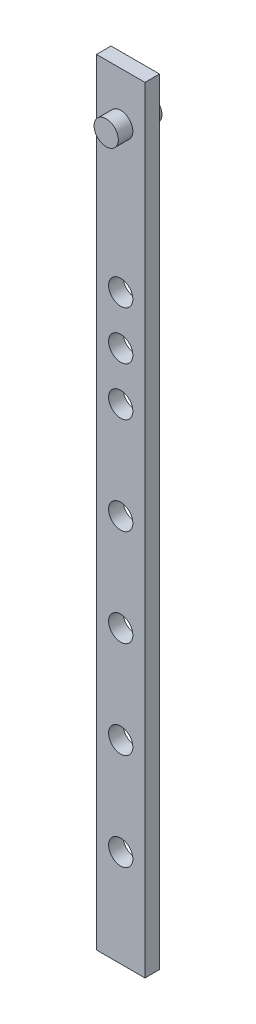
SolidWorks part; units mm, degrees
ref_plane "前基準面" through (0, 0, 0) normal (0, 0, 1) x (1, 0, 0)
ref_plane "上基準面" through (0, 0, 0) normal (0, 1, 0) x (1, 0, 0)
ref_plane "右基準面" through (0, 0, 0) normal (1, 0, 0) x (0, 0, -1)
sketch "草圖1" plane through (0, 0, 0) normal (0, 0, 1) x (1, 0, 0)
  line L0 (0, -80) -> (0, 80) construction
  line L1 (-5, -80) -> (5, -80)
  line L2 (-5, -80) -> (-5, 80)
  line L3 (-5, 80) -> (5, 80)
  line L4 (5, -80) -> (5, 80)
  line L5 (-5, -80) -> (5, 80) construction
  line L6 (-5, 80) -> (5, -80) construction
  circle A0 centre (0, -60) radius 2.5
  circle A1 centre (0, -40) radius 2.5
  circle A2 centre (0, -20) radius 2.5
  circle A3 centre (0, 0) radius 2.5
  circle A4 centre (0, 20) radius 2.5
  circle A5 centre (0, 40) radius 2.5
  circle A6 centre (0, 30) radius 2.5
  point P0 (0, 0)
  dimension "D3" = 20
  dimension "D9" = 5
  dimension "D11" = 10
  dimension "D10" = 5
  dimension "D1" = 160
  dimension "D2" = 10
  dimension "D4" = 20
  dimension "D5" = 20
  dimension "D6" = 20
  dimension "D7" = 20
  dimension "D8" = 20
extrude "填料-伸長1" add sketch "草圖1" along normal blind 3
sketch "草圖2" plane through (0, 0, 3) normal (0, 0, 1) x (1, 0, 0)
  line L1 (5, 80) -> (-5, 80) construction
  circle A0 centre (0, 70) radius 2.5
  dimension "D1" = 5
  dimension "D2" = 10
extrude "填料-伸長2" add sketch "草圖2" against normal blind 6 and the other way blind 3
